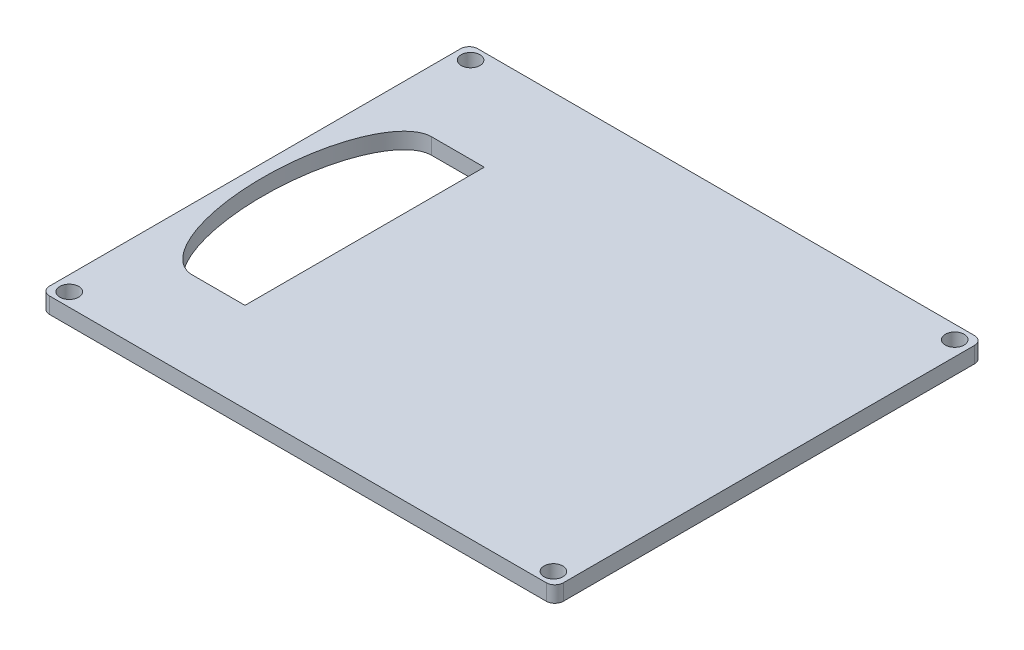
SolidWorks part; units mm, degrees
ref_plane "Front Plane" through (0, 0, 0) normal (0, 0, 1) x (1, 0, 0)
ref_plane "Top Plane" through (0, 0, 0) normal (0, 1, 0) x (1, 0, 0)
ref_plane "Right Plane" through (0, 0, 0) normal (1, 0, 0) x (0, 0, -1)
sketch "Sketch1" plane through (0, 0, 0) normal (0, 1, 0) x (1, 0, 0)
  line L1 (-76.2, 63.5) -> (76.2, 63.5)
  line L2 (-76.2, 63.5) -> (-76.2, -63.5)
  line L3 (-76.2, -63.5) -> (76.2, -63.5)
  line L4 (76.2, 63.5) -> (76.2, -63.5)
  line L5 (-76.2, 63.5) -> (76.2, -63.5) construction
  line L6 (-76.2, -63.5) -> (76.2, 63.5) construction
  point P0 (0, 0)
  dimension "D1" = 152.4
  dimension "D2" = 127
extrude "Boss-Extrude1" add sketch "Sketch1" along normal blind 4.7625
sketch "Sketch2" plane through (0, 4.7625, 0) normal (0, 1, 0) x (1, 0, 0)
  circle A0 centre (71.7948, -59.5104) radius 2.794
  circle A1 centre (71.7948, 59.5104) radius 2.794
  dimension "D1" = 5.588
  dimension "D2" = 5.588
extrude "Cut-Extrude1" cut sketch "Sketch2" against normal through all
sketch "Sketch3" plane through (0, 0, 63.5) normal (0, 0, 1) x (1, 0, 0)
  line L0 (0, 4.7625) -> (0, -1.818) construction
  line L1 (-76.2, 4.7625) -> (76.2, 4.7625) construction
  line L2 (0, 4.7625) -> (0, 0) construction
ref_plane "Plane1" through (0, 0, 0) normal (1, 0, 0) x (0, -1, 0)
mirror "Mirror1" about plane through (0, 0, 0) normal (1, 0, 0) of "Cut-Extrude1"
fillet "Fillet1" radius 2.54 4 edges at (-76.2, 2.3813, 63.5) (76.2, 2.3813, 63.5) (76.2, 2.3813, -63.5) (-76.2, 2.3813, -63.5)
sketch "Sketch4" plane through (0, 4.7625, 0) normal (0, 1, 0) x (1, 0, 0)
  line L1 (-57.8579, 34.0444) -> (-42.2579, 34.0444)
  line L2 (-57.8579, 34.0444) -> (-57.8579, -36.9245)
  line L3 (-57.8579, -36.9245) -> (-42.2579, -36.9245)
  line L4 (-42.2579, 34.0444) -> (-42.2579, -36.9245)
extrude "Cut-Extrude2" cut sketch "Sketch4" against normal through all
sketch "Sketch5" plane through (0, 4.7625, 0) normal (0, 1, 0) x (1, 0, 0)
  line L0 (-57.8579, 34.0444) -> (-57.8579, -36.9245) construction
  ellipse E0 centre (-57.8579, -1.4401) end of major axis (-57.8579, -36.9245) minor radius 14.605
  dimension "D1" = 29.21
extrude "Cut-Extrude3" cut sketch "Sketch5" against normal through all
